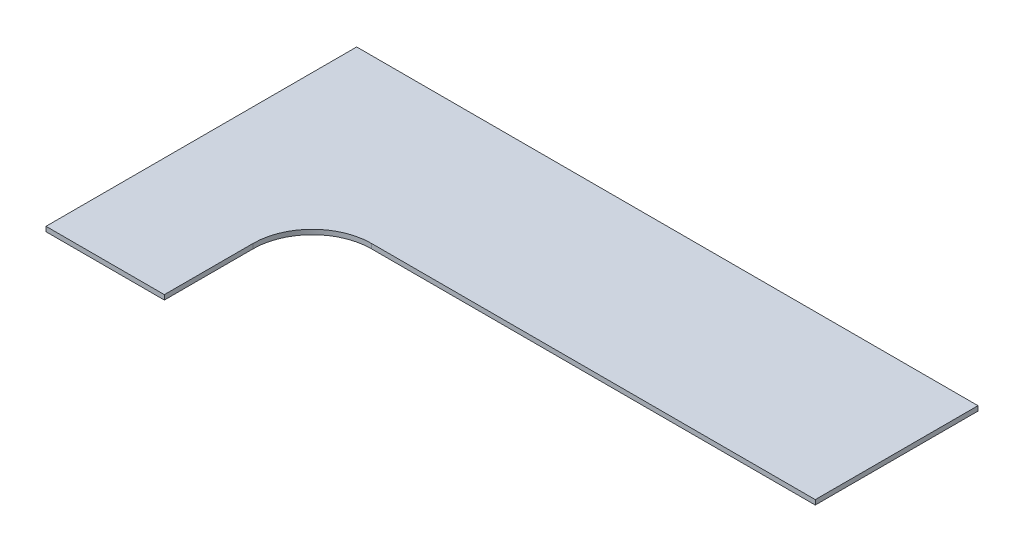
SolidWorks part; units mm, degrees
ref_plane "Ebene vorne" through (0, 0, 0) normal (0, 0, 1) x (1, 0, 0)
ref_plane "Ebene oben" through (0, 0, 0) normal (0, 1, 0) x (1, 0, 0)
ref_plane "Ebene rechts" through (0, 0, 0) normal (1, 0, 0) x (0, 0, -1)
sketch "Skizze1" plane through (0, 0, 0) normal (0, 1, 0) x (1, 0, 0)
  line L0 (0, 0) -> (2100, 0)
  line L1 (2100, 0) -> (2100, -550)
  line L2 (2100, -550) -> (600, -550)
  line L3 (400, -750) -> (400, -1050)
  line L4 (400, -1050) -> (0, -1050)
  line L5 (0, -1050) -> (0, 0)
  arc A0 (600, -550) -> (400, -750) centre (600, -750) ccw
  dimension "D3" = 200
  dimension "D1" = 550
  dimension "D2" = 400
  dimension "D4" = 2100
  dimension "D5" = 500
extrude "Aufsatz-Linear austragen1" add sketch "Skizze1" along normal blind 16
